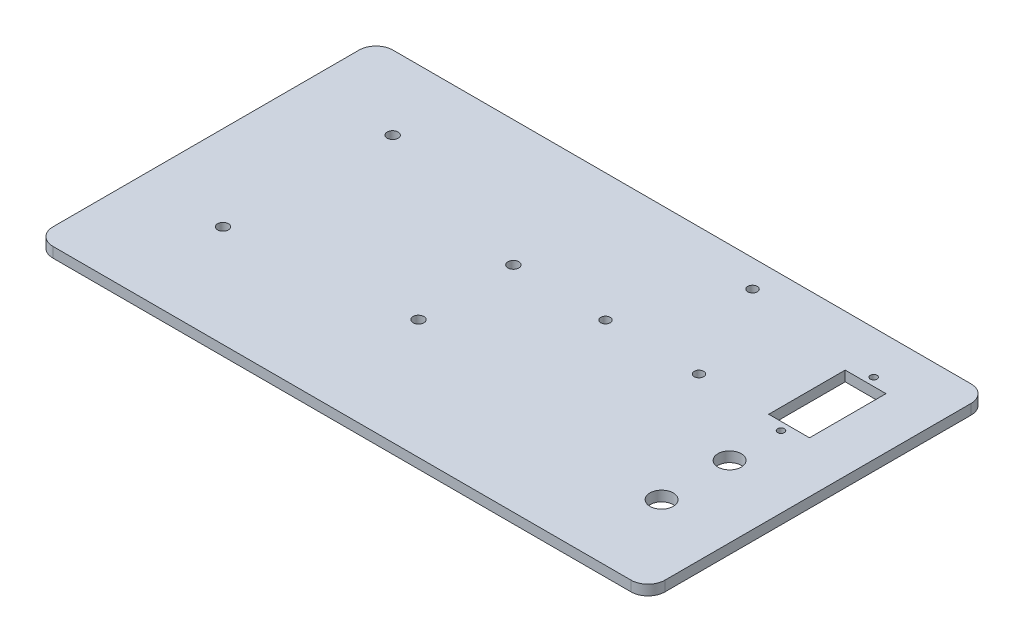
SolidWorks part; units mm, degrees
ref_plane "Front Plane" through (0, 0, 0) normal (0, 0, 1) x (1, 0, 0)
ref_plane "Top Plane" through (0, 0, 0) normal (0, 1, 0) x (1, 0, 0)
ref_plane "Right Plane" through (0, 0, 0) normal (1, 0, 0) x (0, 0, -1)
sketch "Sketch1" plane through (0, 0, 0) normal (0, 1, 0) x (1, 0, 0)
  line L1 (-90, 50) -> (90, 50)
  line L2 (-90, 50) -> (-90, -50)
  line L3 (-90, -50) -> (90, -50)
  line L4 (90, 50) -> (90, -50)
  line L5 (-90, 50) -> (90, -50) construction
  line L6 (-90, -50) -> (90, 50) construction
  point P0 (0, 0)
  dimension "D1" = 180
  dimension "D2" = 100
extrude "Boss-Extrude1" add sketch "Sketch1" along normal blind 3
sketch "Sketch2" plane through (0, 3, 0) normal (0, 1, 0) x (1, 0, 0)
  line L0 (-90, 50) -> (-90, -50) construction
  line L1 (-90, -50) -> (90, -50) construction
  line L2 (-65, -20) -> (-65, 28.3) construction
  line L3 (-65, -20) -> (52.1033, -20) construction
  circle A0 centre (-65, -20) radius 1.6
  circle A1 centre (-63.4, 28.3) radius 1.6
  circle A2 centre (-12.6, 13) radius 1.6
  circle A3 centre (-12.6, -14.9) radius 1.6
  dimension "D2" = 30
  dimension "D4" = 3.2
  dimension "D5" = 50.8
  dimension "D6" = 27.9
  dimension "D7" = 5.1
  dimension "D3" = 48.3
  dimension "D1" = 25
extrude "Cut-Extrude1" cut sketch "Sketch2" against normal blind 10
fillet "Fillet1" radius 5 4 edges at (-90, 1.5, -50) (-90, 1.5, 50) (90, 1.5, 50) (90, 1.5, -50)
sketch "Sketch3" plane through (0, 3, 0) normal (0, 1, 0) x (1, 0, 0)
  line L0 (85, 50) -> (-85, 50) construction
  line L1 (63, 35) -> (75, 35)
  line L2 (63, 35) -> (63, 12.5)
  line L3 (63, 12.5) -> (75, 12.5)
  line L4 (75, 35) -> (75, 12.5)
  line L5 (63, 35) -> (75, 12.5) construction
  line L6 (63, 12.5) -> (75, 35) construction
  line L7 (90, -45) -> (90, 45) construction
  line L8 (75, 39.775) -> (75, 6.6405) construction
  line L9 (69, 37.38) -> (69, -57.8737) construction
  line L10 (-85, -50) -> (85, -50) construction
  line L11 (75, 12.5) -> (10, 12.5) construction
  line L12 (2.0276, 42) -> (55.4724, 42) construction
  line L13 (15, 12.5) -> (15, 50) construction
  circle A0 centre (69, 10.12) radius 1
  circle A1 centre (69, 37.38) radius 1
  circle A4 centre (69, -25) radius 3.43
  circle A5 centre (69, -5) radius 3.43
  circle A6 centre (42.5, 12.5) radius 1.4
  circle A7 centre (15, 12.5) radius 1.4
  circle A8 centre (28.75, 42) radius 1.4
  point P0 (69, 23.75)
  point P11 (69, 12.5)
  dimension "D6" = 2
  dimension "D8" = 6
  dimension "D10" = 6.86
  dimension "D11" = 25
  dimension "D12" = 45
  dimension "D13" = 21
  dimension "D14" = 27.5
  dimension "D15" = 2.8
  dimension "D17" = 75
  dimension "D18" = 13.75
  dimension "D1" = 12
  dimension "D2" = 15
  dimension "D3" = 15
  dimension "D4" = 22.5
  dimension "D5" = 2.38
  dimension "D7" = 2.38
  dimension "D9" = 6
  dimension "D16" = 8
extrude "Cut-Extrude2" cut sketch "Sketch3" against normal up to surface (3 mm away) up to face at (-65, 0, 21.6)
